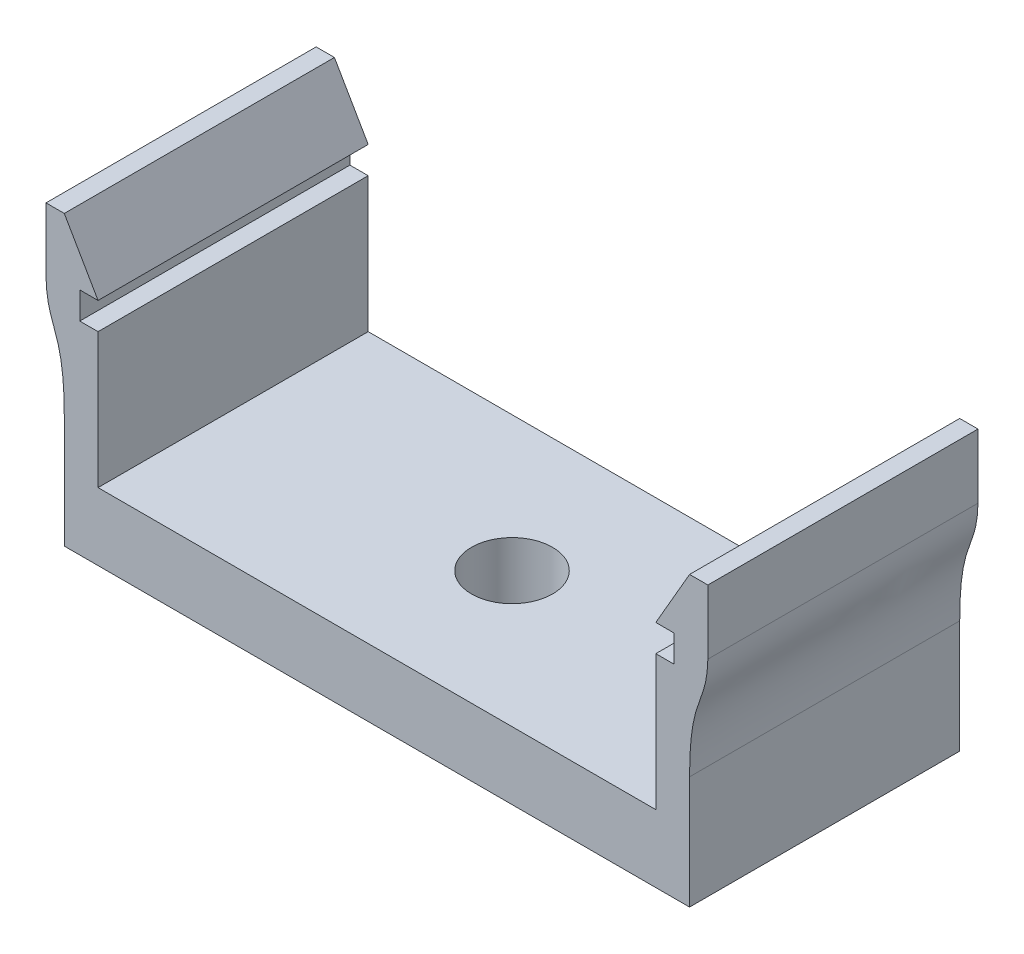
SolidWorks part; units mm, degrees
ref_plane "Front Plane" through (0, 0, 0) normal (0, 0, 1) x (1, 0, 0)
ref_plane "Top Plane" through (0, 0, 0) normal (0, 1, 0) x (1, 0, 0)
ref_plane "Right Plane" through (0, 0, 0) normal (1, 0, 0) x (0, 0, -1)
sketch "Sketch1" plane through (0, 0, 0) normal (0, 0, 1) x (1, 0, 0)
  line L0 (0, 0) -> (0, 3.175)
  line L1 (0, 3.175) -> (-13.1103, 3.175)
  line L2 (-13.1103, 3.175) -> (-13.1103, 9.525)
  line L3 (-13.1103, 9.525) -> (-13.97, 9.525)
  line L4 (-13.97, 9.525) -> (-13.97, 10.795)
  line L5 (-13.97, 10.795) -> (-13.1103, 10.795)
  line L6 (-13.1103, 10.795) -> (-14.6978, 13.5446)
  line L9 (-14.6978, 0) -> (0, 0)
  line L10 (-14.6978, 0) -> (-14.6978, 5.3041)
  line L12 (-15.5575, 10.5249) -> (-15.5575, 13.5446)
  line L13 (-15.5575, 13.5446) -> (-14.6978, 13.5446)
  spline S0 degree 3 poles (-14.6978, 5.3041) (-14.6978, 8.8598) (-15.5019, 8.4361) (-15.5575, 10.5249) knots 0 0 0 0 1 1 1 1
  point P10 (-14.5589, 10.0098)
  point P14 (-12.9714, 10.795)
  point P15 (-14.6459, 7.8982)
  point P16 (-15.5575, 12.0363)
  point P17 (-14.725, 6.5616)
  point P18 (-15.5575, 9.525)
  point P19 (-14.6957, 5.1368)
  point P20 (-14.6978, 5.3041)
  point P21 (-15.5575, 10.1087)
  point P22 (-15.5575, 10.5249)
  dimension "D1" = 3.175
  dimension "D2" = 1.5875
  dimension "D3" = 1.5875
  dimension "D4" = 13.97
  dimension "D5" = 6.35
  dimension "D6" = 1.27
  dimension "D7" = 60
extrude "Boss-Extrude1" add sketch "Sketch1" along normal blind 12.7
mirror "Mirror1" about plane through (0, 0, 0) normal (1, 0, 0) of "Boss-Extrude1"
sketch "Sketch2" plane through (0, 3.175, 0) normal (0, 1, 0) x (1, 0, 0)
  line L0 (0, 0) -> (0, -12.7) construction
  line L1 (13.1103, 0) -> (-13.1103, 0) construction
  line L2 (13.1103, -12.7) -> (-13.1103, -12.7) construction
  circle A0 centre (0, -6.35) radius 1.905
  dimension "D1" = 3.81
extrude "Cut-Extrude1" cut sketch "Sketch2" against normal blind 12.7
